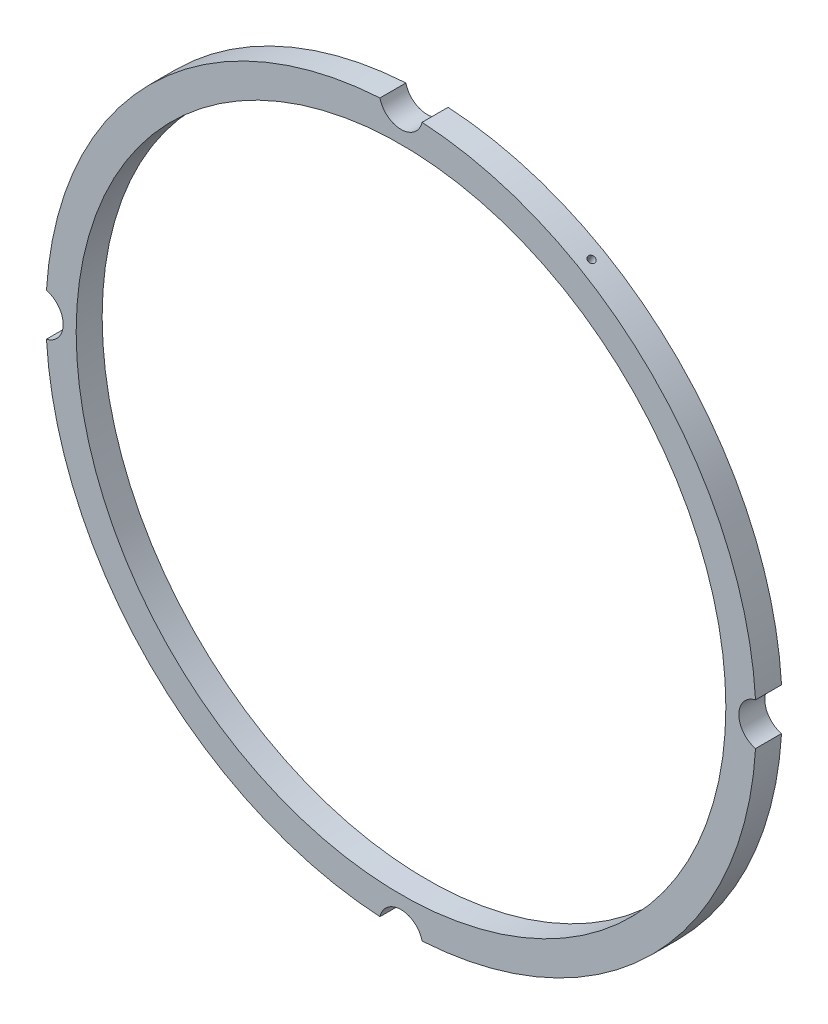
SolidWorks part; units mm, degrees
ref_plane "Front Plane" through (0, 0, 0) normal (0, 0, 1) x (1, 0, 0)
ref_plane "Top Plane" through (0, 0, 0) normal (0, 1, 0) x (1, 0, 0)
ref_plane "Right Plane" through (0, 0, 0) normal (1, 0, 0) x (0, 0, -1)
sketch "Sketch1" plane through (0, 0, 0) normal (0, 0, 1) x (1, 0, 0)
  circle A0 centre (0, 0) radius 75
  circle A1 centre (0, 0) radius 82
extrude "Boss-Extrude1" add sketch "Sketch1" along normal blind 6
sketch "Sketch2" plane through (0, 0, 6) normal (0, 0, 1) x (1, 0, 0)
  circle A0 centre (0, 83) radius 5
extrude "Cut-Extrude1" cut sketch "Sketch2" against normal through all
pattern_circular "CirPattern1" count 4 every 90 about axis through (0, 0, 0) along (0, 0, 1) of "Cut-Extrude1"
hole_wizard "M2x0.4 Tapped Hole1" positions "3DSketch1" profile "Sketch3" tap size "M2x0.4" standard "ANSI Metric"
sketch3d "3DSketch1"
  point P0 (41, 71.0141, 3)
sketch "Sketch3" plane through (41, 71.0141, 3) normal (0, 0, 1) x (-0.866, 0.5, 0)
  line L0 (0, 0) -> (0, 10.4807)
  line L1 (0, 10.4807) -> (0.8, 10)
  line L2 (0.8, 10) -> (0.8, 0)
  line L5 (0.8, 0) -> (0, 0)
  line L10 (0, 10.4807) -> (-0.8, 10) construction
  line L11 (0, -6.35) -> (0, 107.95) construction
  dimension "Tap Drill Dia." = 1.6
  dimension "Tap Drill Depth" = 10
  dimension "Drill Angle" = 118
cosmetic thread "Hole Thread1" parameters "D1"=4, "D2"=2
